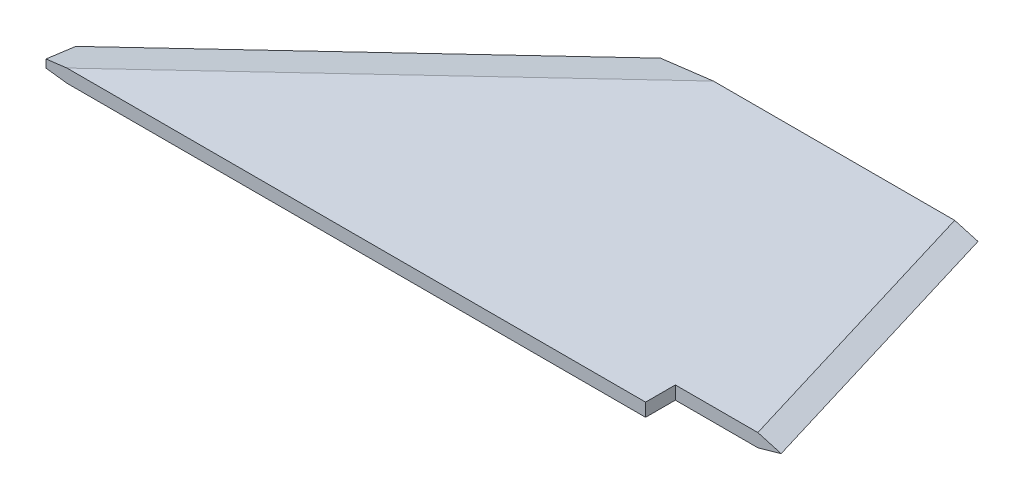
SolidWorks part; units mm, degrees
ref_plane "Front Plane" through (0, 0, 0) normal (0, 0, 1) x (1, 0, 0)
ref_plane "Top Plane" through (0, 0, 0) normal (0, 1, 0) x (1, 0, 0)
ref_plane "Right Plane" through (0, 0, 0) normal (1, 0, 0) x (0, 0, -1)
sketch "Sketch2" plane through (0, 0, 0) normal (0, 1, 0) x (1, 0, 0)
  line L0 (0, 0) -> (254, 0)
  line L1 (0, 0) -> (0, 132.7069)
  line L2 (0, 0) -> (108.966, 101.6124)
  line L3 (108.966, 101.6124) -> (223.266, 101.6124)
  line L5 (223.266, 101.6124) -> (254, 0)
  line L6 (0, 0) -> (215.9, 0)
  line L7 (0, 0) -> (0, -10.7188)
  line L8 (0, -10.7188) -> (215.9, -10.7188)
  line L9 (215.9, 0) -> (215.9, -10.7188)
  dimension "D1" = 254
  dimension "D2" = 47
  dimension "D3" = 114.3
  dimension "D4" = 108.966
  dimension "D5" = 101.6124
  dimension "D6" = 10.7188
  dimension "D7" = 215.9
extrude "Boss-Extrude1" add sketch "Sketch2" along normal blind 4.7498 contours L2 L3 L5 L0 | L7 L6 L9 L8
ref_plane "Plane4" through (108.966, 0, -101.6124) normal (-0.7314, 0, 0.682) x (0.682, 0, 0.7314)
sketch "Sketch9" plane through (108.966, 0, -101.6124) normal (-0.7314, 0, 0.682) x (0.682, 0, 0.7314)
  line L0 (0, 2.3749) -> (12.9927, 0)
  line L1 (0, 4.7498) -> (0, 0) construction
  line L2 (0, 0) -> (7.8392, 0) construction
  line L4 (0, 4.7498) -> (7.8392, 4.7498) construction
  line L5 (12.9927, 4.7498) -> (0, 2.3749)
  line L6 (12.9927, 4.7498) -> (12.9927, 7.4487)
  line L7 (12.9927, 7.4487) -> (-2.3775, 7.4487)
  line L8 (-2.3775, 7.4487) -> (-2.3775, -1.9753)
  line L9 (-2.3775, -1.9753) -> (12.9927, -1.9753)
  line L10 (12.9927, -1.9753) -> (12.9927, 0)
  dimension "D1" = 13.208
  dimension "D2" = 20.717
ref_plane "Plane5" through (21.2893, 0, 70.3864) normal (-0.2895, 0, -0.9572) x (-0.9572, 0, 0.2895)
sketch "Sketch11" plane through (21.2893, 0, 70.3864) normal (-0.2895, 0, -0.9572) x (-0.9572, 0, 0.2895)
  line L0 (-243.1224, 2.3749) -> (-235.0839, 4.7498)
  line L1 (-243.1224, 4.7498) -> (-243.1224, 0) construction
  line L2 (-133.7173, 4.7498) -> (-243.1224, 4.7498) construction
  line L4 (-133.7173, 0) -> (-243.1224, 0) construction
  line L5 (-235.0839, 0) -> (-243.1224, 2.3749)
  line L6 (-235.0839, 4.7498) -> (-235.0839, 6.7357)
  line L7 (-235.0839, 6.7357) -> (-246.0086, 6.7357)
  line L8 (-235.0839, 0) -> (-235.0839, -1.6837)
  line L9 (-235.0839, -1.6837) -> (-246.0086, -1.6837)
  line L10 (-246.0086, -1.6837) -> (-246.0086, 6.7357)
  dimension "D1" = 8.382
  dimension "D2" = 32.918
extrude "Cut-Extrude1" cut sketch "Sketch11" along normal blind 127 contours L7 L10 L9 L8 L5 L0 L6
extrude "Cut-Extrude2" cut sketch "Sketch9" against normal through all both and the other way through all
